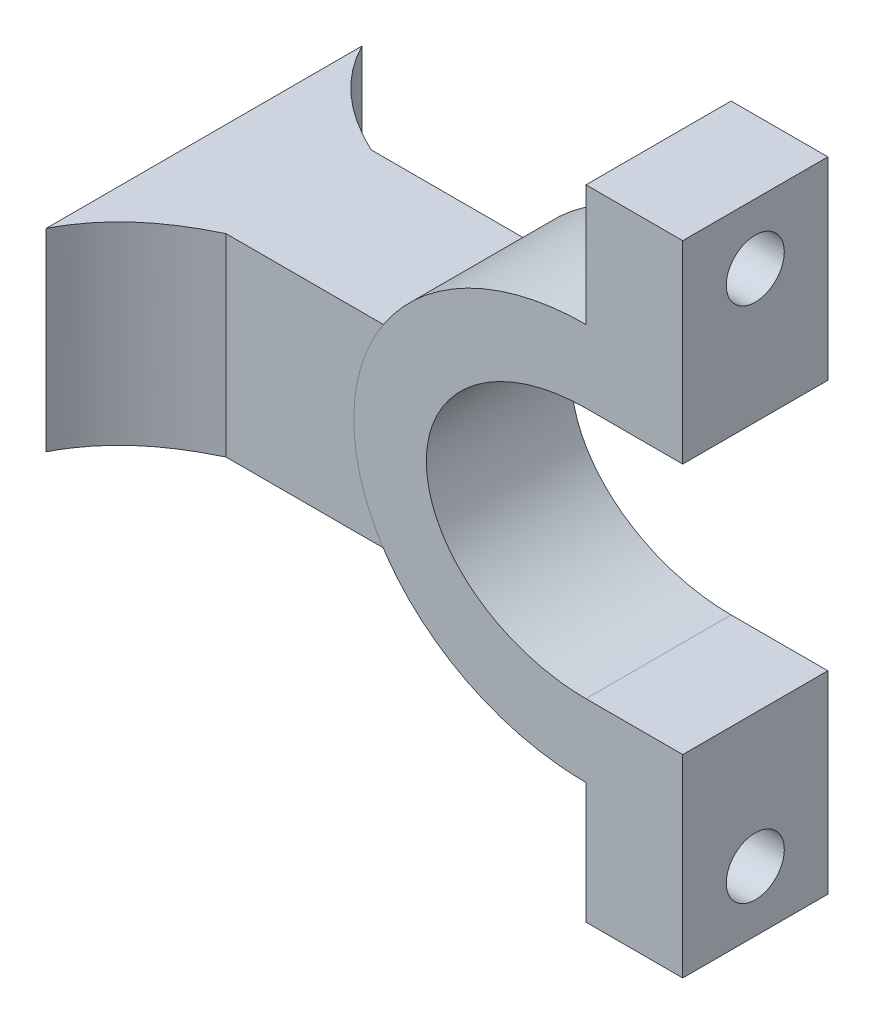
SolidWorks part; units mm, degrees
ref_plane "Front Plane" through (0, 0, 0) normal (0, 0, 1) x (1, 0, 0)
ref_plane "Top Plane" through (0, 0, 0) normal (0, 1, 0) x (1, 0, 0)
ref_plane "Right Plane" through (0, 0, 0) normal (1, 0, 0) x (0, 0, -1)
sketch "Sketch1" plane through (0, 0, 0) normal (0, 0, 1) x (1, 0, 0)
  line L0 (0, 20.5) -> (0, -20.5)
  ellipse E0 centre (0, 0) end of major axis (16.5, 0) minor radius 13
  ellipse E1 centre (0, 0) end of major axis (24, 0) minor radius 20.5
  dimension "D1" = 26
  dimension "D2" = 33
  dimension "D3" = 41
  dimension "D4" = 48
extrude "Boss-Extrude1" add sketch "Sketch1" along normal blind 15 contours L0 E1 E0
ref_plane "Plane1" through (-24, 0, 0) normal (1, 0, 0) x (0, 0, -1)
sketch "Sketch2" plane through (-24, 0, 0) normal (1, 0, 0) x (0, 0, -1)
  line L2 (0.0273, 10) -> (-14.9727, 10)
  line L3 (0.0273, 10) -> (0.0273, -10)
  line L4 (0.0273, -10) -> (-14.9727, -10)
  line L5 (-14.9727, 10) -> (-14.9727, -10)
  line L6 (0.0273, 10) -> (-14.9727, -10) construction
  line L7 (0.0273, -10) -> (-14.9727, 10) construction
  point P2 (-7.4727, 0)
  dimension "D1" = 15
  dimension "D2" = 20
extrude "Boss-Extrude2" add sketch "Sketch2" against normal blind 23 and the other way blind 5
sketch "Sketch3" plane through (0, 0, 0) normal (1, 0, 0) x (0, 0, -1)
  line L0 (0, 0) -> (-15, 0) construction
  line L1 (-15, 13) -> (0, 13)
  line L2 (-15, 13) -> (-15, 33)
  line L3 (-15, 33) -> (0, 33)
  line L4 (0, 13) -> (0, 33)
  line L5 (-15, 13) -> (-15, -13) construction
  line L6 (-15, -33) -> (0, -33)
  line L7 (0, -13) -> (0, -33)
  line L8 (-15, -13) -> (0, -13)
  line L9 (-15, -13) -> (-15, -33)
  dimension "D1" = 20
extrude "Boss-Extrude3" add sketch "Sketch3" along normal blind 10
sketch "Sketch4" plane through (0, 0, 0) normal (-1, 0, 0) x (0, 0, 1)
  line L0 (0, 33) -> (15, 20.5) construction
  line L1 (0, 20.5) -> (15, 33) construction
  line L2 (0, 33) -> (15, 33) construction
  line L3 (0, 0) -> (14.9727, 0) construction
  line L4 (14.9727, 10) -> (14.9727, -10) construction
  circle A0 centre (7.5, 26.75) radius 3
  circle A1 centre (7.5, -26.75) radius 3
  dimension "D1" = 6
extrude "Cut-Extrude1" cut sketch "Sketch4" against normal through all
sketch "Sketch5" plane through (0, -10, 0) normal (0, -1, 0) x (1, 0, 0)
  line L0 (-47, 14.9727) -> (-47, 23.7948)
  line L1 (-47, 23.7948) -> (-44.4142, 18.7816) construction
  line L2 (-44.4142, 18.7816) -> (-40.1109, 16.3726) construction
  line L3 (-40.1109, 16.3726) -> (-37.232, 14.9727) construction
  line L5 (-20.9509, 14.9727) -> (-47, 14.9727) construction
  line L6 (-47, 7.4727) -> (-43.9126, 7.4727) construction
  line L7 (-47, 14.9727) -> (-47, -0.0273) construction
  line L8 (-47, -0.0273) -> (-47, -8.8495)
  line L9 (-47, -8.8495) -> (-44.4142, -3.8362) construction
  line L10 (-44.4142, -3.8362) -> (-40.1109, -1.4272) construction
  line L11 (-40.1109, -1.4272) -> (-37.232, -0.0273) construction
  line L12 (-47, -0.0273) -> (-37.232, -0.0273)
  line L13 (-47, 14.9727) -> (-37.232, 14.9727)
  spline S0 degree 3 poles (-47, 23.7948) (-44.4142, 18.7816) (-40.1109, 16.3726) (-37.232, 14.9727) knots 0 0 0 0 1 1 1 1
  spline S1 degree 3 poles (-47, -8.8495) (-44.4142, -3.8362) (-40.1109, -1.4272) (-37.232, -0.0273) knots 0 0 0 0 1 1 1 1
extrude "Boss-Extrude4" add sketch "Sketch5" against normal blind 20
